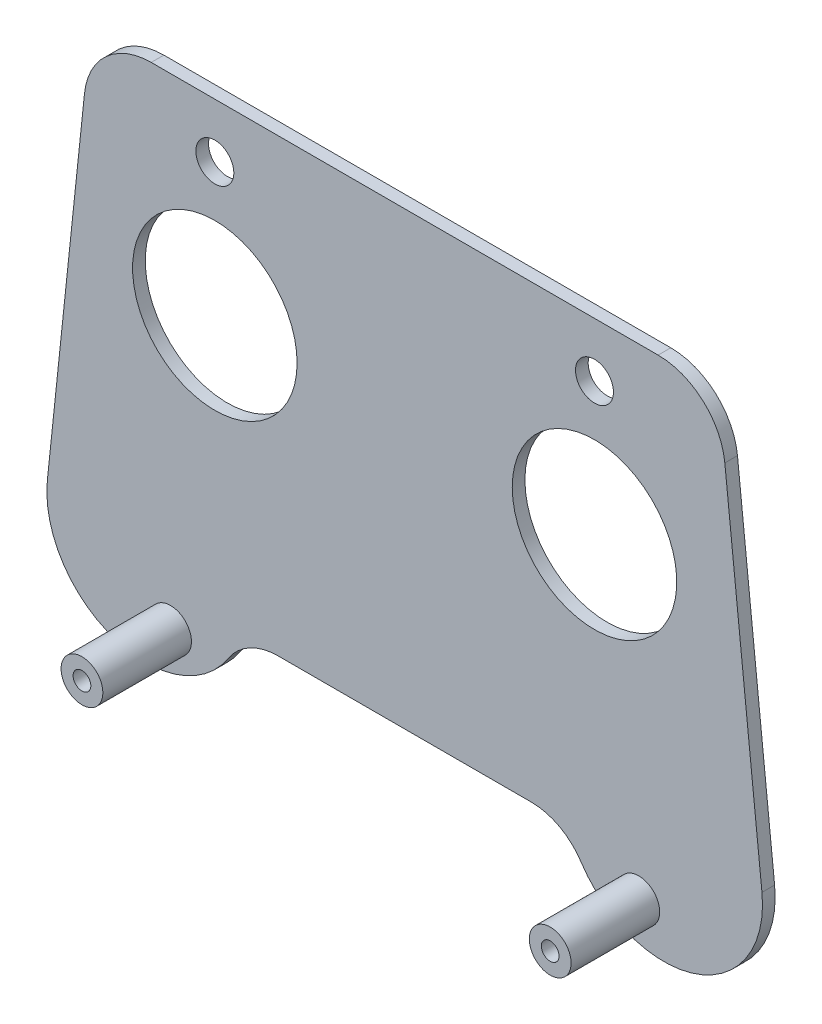
SolidWorks part; units mm, degrees
ref_plane "前视基准面" through (0, 0, 0) normal (0, 0, 1) x (1, 0, 0)
ref_plane "上视基准面" through (0, 0, 0) normal (0, 1, 0) x (1, 0, 0)
ref_plane "右视基准面" through (0, 0, 0) normal (1, 0, 0) x (0, 0, -1)
other "Configuration Table"
sketch "Sketch1" plane through (0, 0, 0) normal (0, 0, 1) x (1, 0, 0)
  line L5 (-9.4677, 47.3762) -> (-9.4677, -41.1708) construction
  line L6 (30.587, 28.8292) -> (-49.5225, 28.8292) construction
  line L8 (-59.4677, 19.8745) -> (-65.3364, -35.9625) construction
  line L10 (-29.4677, -41.1708) -> (10.5323, -41.1708) construction
  line L11 (40.5323, 19.8745) -> (46.401, -35.9625) construction
  line L12 (30.587, 29.4292) -> (-49.5225, 29.4292)
  line L13 (-60.0645, 19.9372) -> (-65.9332, -35.8998)
  line L14 (-29.4677, -41.7708) -> (10.5323, -41.7708)
  line L15 (41.129, 19.9372) -> (46.9977, -35.8998)
  line L16 (-59.4677, 19.8745) -> (-59.4677, -5.7934) construction
  line L18 (-39.4677, -0.1708) -> (-39.4677, 22.5604) construction
  line L20 (-39.4677, 28.8292) -> (-39.4677, 12.8292) construction
  arc A6 (-59.4677, 19.8745) -> (-49.5225, 28.8292) centre (-49.5225, 18.8292) cw construction
  arc A7 (-65.3364, -35.9625) -> (-37.8481, -45.7147) centre (-50.4186, -37.5304) ccw construction
  arc A8 (-29.4677, -41.1708) -> (-37.8481, -45.7147) centre (-29.4677, -51.1708) ccw construction
  arc A9 (10.5323, -41.1708) -> (18.9126, -45.7147) centre (10.5323, -51.1708) cw construction
  arc A10 (46.401, -35.9625) -> (18.9126, -45.7147) centre (31.4831, -37.5304) cw construction
  arc A11 (40.5323, 19.8745) -> (30.587, 28.8292) centre (30.587, 18.8292) ccw construction
  arc A12 (-60.0645, 19.9372) -> (-49.5225, 29.4292) centre (-49.5225, 18.8292) cw
  arc A13 (-65.9332, -35.8998) -> (-37.3453, -46.042) centre (-50.4186, -37.5304) ccw
  arc A14 (-29.4677, -41.7708) -> (-37.3453, -46.042) centre (-29.4677, -51.1708) ccw
  arc A15 (10.5323, -41.7708) -> (18.4098, -46.042) centre (10.5323, -51.1708) cw
  arc A16 (46.9977, -35.8998) -> (18.4098, -46.042) centre (31.4831, -37.5304) cw
  arc A17 (41.129, 19.9372) -> (30.587, 29.4292) centre (30.587, 18.8292) ccw
  circle A19 centre (-39.4677, -0.1708) radius 13
  circle A20 centre (20.5323, -0.1708) radius 13
  circle A21 centre (-39.4677, 20.8292) radius 3
  circle A22 centre (20.5323, 20.8292) radius 3
  point P23 (-9.4677, 28.8292)
  dimension "D3" = 15
  dimension "D4" = 10
  dimension "D7" = 40
  dimension "D8" = 0.6
  dimension "D5" = 50
  dimension "D2" = 10
  dimension "D11" = 26
  dimension "D12" = 6
  dimension "D1" = 96
  dimension "D6" = 70
  dimension "D9" = 29
  dimension "D10" = 20
  dimension "D13" = 8
extrude "Boss-Extrude1" add sketch "Sketch1" along normal blind 2
sketch "Sketch2" plane through (0, 0, 2) normal (0, 0, 1) x (1, 0, 0)
  line L0 (-29.4677, -41.7708) -> (-65.4312, -41.7708) construction
  line L1 (-29.4677, -41.7708) -> (10.5323, -41.7708) construction
  line L2 (-46.4677, -25.898) -> (-46.4677, -54.8364) construction
  line L3 (-9.4677, 29.4292) -> (-9.4677, -41.7708) construction
  line L4 (30.587, 29.4292) -> (-49.5225, 29.4292) construction
  line L5 (-9.4677, -6.1708) -> (-70.1972, -6.1708) construction
  arc A0 (-65.9332, -35.8998) -> (-37.3453, -46.042) centre (-50.4186, -37.5304) ccw construction
  circle A1 centre (-46.4677, -46.6708) radius 3.3
  circle A2 centre (27.5323, -46.6708) radius 3.3
  arc A4 (-29.4677, -41.7708) -> (-37.3453, -46.042) centre (-29.4677, -51.1708) ccw construction
  dimension "D3" = 6.6
  dimension "D1" = 37
  dimension "D2" = 40.5
extrude "Boss-Extrude2" add sketch "Sketch2" along normal blind 14
sketch "Sketch3" plane through (0, 0, 16) normal (0, 0, 1) x (1, 0, 0)
  line L0 (-9.4677, 29.4292) -> (-9.4677, -45.6796) construction
  line L1 (30.587, 29.4292) -> (-49.5225, 29.4292) construction
  circle A0 centre (-46.4677, -46.6708) radius 1.4
  circle A1 centre (27.5323, -46.6708) radius 1.4
extrude "Cut-Extrude1" cut sketch "Sketch3" against normal blind 10
